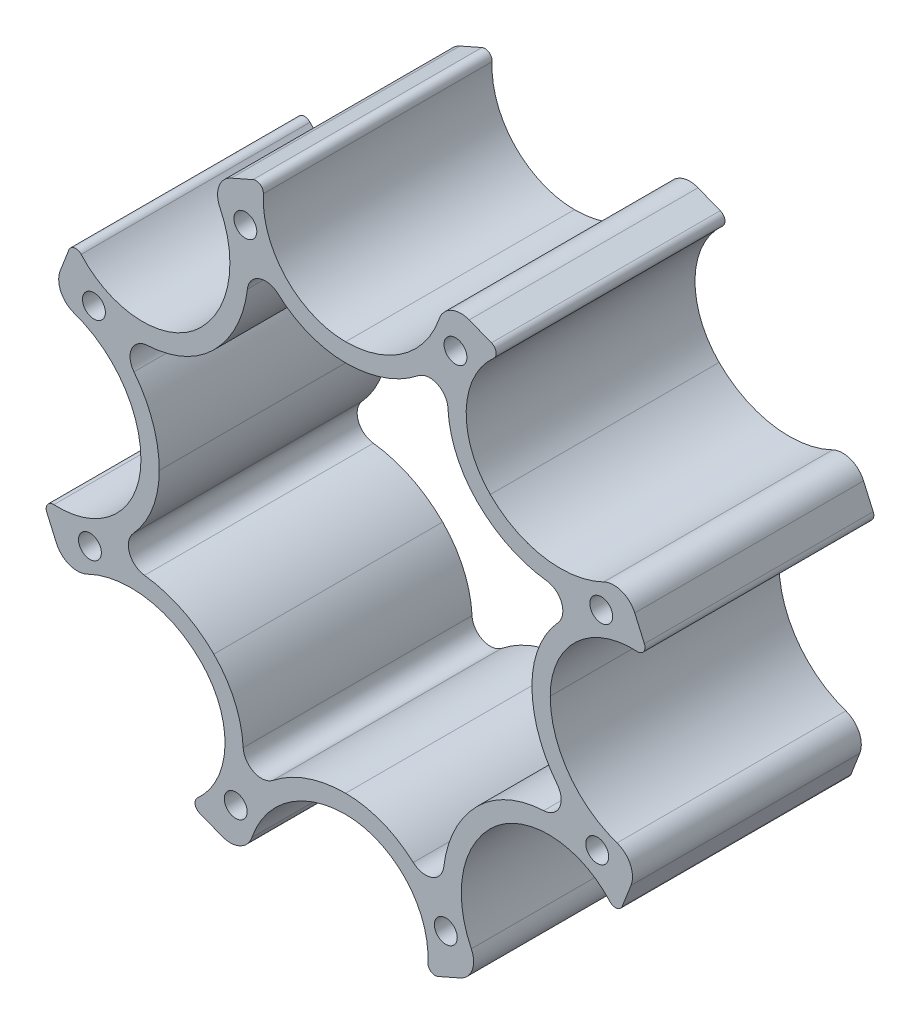
SolidWorks part; units mm, degrees
material "6061-T6 (SS)"
ref_plane "前视基准面" through (0, 0, 0) normal (0, 0, 1) x (1, 0, 0)
ref_plane "上视基准面" through (0, 0, 0) normal (0, 1, 0) x (1, 0, 0)
ref_plane "右视基准面" through (0, 0, 0) normal (1, 0, 0) x (0, 0, -1)
sketch "草图1" plane through (0, 0, 0) normal (0, 0, 1) x (1, 0, 0)
  line L0 (0, 31.3575) -> (0, 0) construction
  line L1 (0, 0) -> (22.1731, 22.1731) construction
  line L4 (0, 31.3575) -> (22.1731, 22.1731) construction
  line L6 (11.6409, 26.5357) -> (12.5976, 28.8454) construction
  line L7 (22.2808, 22.9688) -> (16.1797, 28.8872) construction
  line L8 (22.2808, 22.9688) -> (28.5472, 29.4288) construction
  line L9 (15.9368, 30.2296) -> (13.5034, 31.1755)
  line L17 (0, 33.18) -> (0, 31.3575) construction
  line L18 (32.6446, 10.1066) -> (31.5928, 12.4961)
  line L19 (30.2296, -15.9368) -> (31.1755, -13.5034)
  line L20 (10.1066, -32.6446) -> (12.4961, -31.5928)
  line L21 (-15.9368, -30.2296) -> (-13.5034, -31.1755)
  line L22 (-32.6446, -10.1066) -> (-31.5928, -12.4961)
  line L23 (-30.2296, 15.9368) -> (-31.1755, 13.5034)
  line L24 (-10.1066, 32.6446) -> (-12.4961, 31.5928)
  circle A0 centre (0, 0) radius 31.3575 construction
  arc A9 (16.1797, 28.8872) -> (15.8091, 15.8091) centre (22.1731, 22.1731) ccw
  circle A13 centre (0, 0) radius 41 construction
  arc A16 (16.1797, 28.8872) -> (15.9368, 30.2296) centre (15.6469, 29.484) ccw
  arc A17 (13.5034, 31.1755) -> (10.2336, 29.6588) centre (12.5976, 28.8454) ccw
  arc A18 (0, 22.3575) -> (10.2336, 29.6588) centre (0, 33.18) ccw
  arc A19 (15.8091, 15.8091) -> (28.2082, 13.7357) centre (23.4618, 23.4618) ccw
  arc A20 (31.5928, 12.4961) -> (28.2082, 13.7357) centre (29.3046, 11.4889) ccw
  arc A21 (31.8671, 8.9856) -> (32.6446, 10.1066) centre (31.9124, 9.7843) ccw
  arc A22 (31.8671, 8.9856) -> (22.3575, 0) centre (31.3575, 0) ccw
  arc A23 (22.3575, 0) -> (29.6588, -10.2336) centre (33.18, 0) ccw
  arc A24 (31.1755, -13.5034) -> (29.6588, -10.2336) centre (28.8454, -12.5976) ccw
  arc A25 (28.8872, -16.1797) -> (30.2296, -15.9368) centre (29.484, -15.6469) ccw
  arc A26 (28.8872, -16.1797) -> (15.8091, -15.8091) centre (22.1731, -22.1731) ccw
  arc A27 (15.8091, -15.8091) -> (13.7357, -28.2082) centre (23.4618, -23.4618) ccw
  arc A28 (12.4961, -31.5928) -> (13.7357, -28.2082) centre (11.4889, -29.3046) ccw
  arc A29 (8.9856, -31.8671) -> (10.1066, -32.6446) centre (9.7843, -31.9124) ccw
  arc A30 (8.9856, -31.8671) -> (0, -22.3575) centre (0, -31.3575) ccw
  arc A31 (0, -22.3575) -> (-10.2336, -29.6588) centre (0, -33.18) ccw
  arc A32 (-13.5034, -31.1755) -> (-10.2336, -29.6588) centre (-12.5976, -28.8454) ccw
  arc A33 (-16.1797, -28.8872) -> (-15.9368, -30.2296) centre (-15.6469, -29.484) ccw
  arc A34 (-16.1797, -28.8872) -> (-15.8091, -15.8091) centre (-22.1731, -22.1731) ccw
  arc A35 (-15.8091, -15.8091) -> (-28.2082, -13.7357) centre (-23.4618, -23.4618) ccw
  arc A36 (-31.5928, -12.4961) -> (-28.2082, -13.7357) centre (-29.3046, -11.4889) ccw
  arc A37 (-31.8671, -8.9856) -> (-32.6446, -10.1066) centre (-31.9124, -9.7843) ccw
  arc A38 (-31.8671, -8.9856) -> (-22.3575, 0) centre (-31.3575, 0) ccw
  arc A39 (-22.3575, 0) -> (-29.6588, 10.2336) centre (-33.18, 0) ccw
  arc A40 (-31.1755, 13.5034) -> (-29.6588, 10.2336) centre (-28.8454, 12.5976) ccw
  arc A41 (-28.8872, 16.1797) -> (-30.2296, 15.9368) centre (-29.484, 15.6469) ccw
  arc A42 (-28.8872, 16.1797) -> (-15.8091, 15.8091) centre (-22.1731, 22.1731) ccw
  arc A43 (-15.8091, 15.8091) -> (-13.7357, 28.2082) centre (-23.4618, 23.4618) ccw
  arc A44 (-12.4961, 31.5928) -> (-13.7357, 28.2082) centre (-11.4889, 29.3046) ccw
  arc A45 (-8.9856, 31.8671) -> (-10.1066, 32.6446) centre (-9.7843, 31.9124) ccw
  arc A46 (-8.9856, 31.8671) -> (0, 22.3575) centre (0, 31.3575) ccw
  point P91 (0, 0)
  point P98 (0, 0)
  dimension "D1" = 9
  dimension "D3" = 45
  dimension "D4" = 8
  dimension "D5" = 9
  dimension "D8" = 82
  dimension "D9" = 9
  dimension "D10" = 2.5
  dimension "D11" = 0.8
  dimension "D2" = 24
  dimension "D6" = 11.4
  dimension "D7" = 2.5
  dimension "D13" = 8.5
extrude "凸台-拉伸1" add sketch "草图1" along normal blind 25
sketch "草图2" plane through (0, 0, 0) normal (0, 0, -1) x (-1, 0, 0)
  line L0 (0, 0) -> (22.3575, 0) construction
  line L1 (0, 0) -> (15.8091, -15.8091) construction
  arc A0 (20.3575, 0) -> (23.2148, -7.3957) centre (31.3575, 0) ccw
  arc A1 (21.9674, -10.7267) -> (14.3949, -14.3949) centre (23.4618, -23.4618) ccw
  arc A2 (21.9674, -10.7267) -> (23.2148, -7.3957) centre (21.7343, -8.7403) ccw
  arc A3 (22.3575, 0) -> (31.8671, -8.9856) centre (31.3575, 0) ccw construction
  arc A4 (14.3949, -14.3949) -> (11.1858, -21.6449) centre (22.1731, -22.1731) ccw
  arc A5 (7.9484, -23.1182) -> (11.1858, -21.6449) centre (9.1881, -21.5488) ccw
  arc A27 (28.2082, -13.7357) -> (15.8091, -15.8091) centre (23.4618, -23.4618) ccw construction
  arc A28 (7.9484, -23.1182) -> (0, -20.3575) centre (0, -33.18) ccw
  arc A29 (0, -20.3575) -> (-7.3957, -23.2148) centre (0, -31.3575) ccw
  arc A30 (-10.7267, -21.9674) -> (-7.3957, -23.2148) centre (-8.7403, -21.7343) ccw
  arc A31 (-10.7267, -21.9674) -> (-14.3949, -14.3949) centre (-23.4618, -23.4618) ccw
  arc A32 (-14.3949, -14.3949) -> (-21.6449, -11.1858) centre (-22.1731, -22.1731) ccw
  arc A33 (-23.1182, -7.9484) -> (-21.6449, -11.1858) centre (-21.5488, -9.1881) ccw
  arc A34 (-23.1182, -7.9484) -> (-20.3575, 0) centre (-33.18, 0) ccw
  arc A35 (-20.3575, 0) -> (-23.2148, 7.3957) centre (-31.3575, 0) ccw
  arc A36 (-21.9674, 10.7267) -> (-23.2148, 7.3957) centre (-21.7343, 8.7403) ccw
  arc A37 (-21.9674, 10.7267) -> (-14.3949, 14.3949) centre (-23.4618, 23.4618) ccw
  arc A38 (-14.3949, 14.3949) -> (-11.1858, 21.6449) centre (-22.1731, 22.1731) ccw
  arc A39 (-7.9484, 23.1182) -> (-11.1858, 21.6449) centre (-9.1881, 21.5488) ccw
  arc A40 (-7.9484, 23.1182) -> (0, 20.3575) centre (0, 33.18) ccw
  arc A41 (0, 20.3575) -> (7.3957, 23.2148) centre (0, 31.3575) ccw
  arc A42 (10.7267, 21.9674) -> (7.3957, 23.2148) centre (8.7403, 21.7343) ccw
  arc A43 (10.7267, 21.9674) -> (14.3949, 14.3949) centre (23.4618, 23.4618) ccw
  arc A44 (14.3949, 14.3949) -> (21.6449, 11.1858) centre (22.1731, 22.1731) ccw
  arc A45 (23.1182, 7.9484) -> (21.6449, 11.1858) centre (21.5488, 9.1881) ccw
  arc A46 (23.1182, 7.9484) -> (20.3575, 0) centre (33.18, 0) ccw
  point P69 (0, 0)
  dimension "D1" = 2
  dimension "D2" = 2
  dimension "D3" = 2
  dimension "D4" = 8
extrude "切除-拉伸1" cut sketch "草图2" against normal through all
sketch "草图3" plane through (0, 0, 25) normal (0, 0, 1) x (1, 0, 0)
  line L8 (15.9368, 30.2296) -> (13.5034, 31.1755)
  line L9 (-10.1066, 32.6446) -> (-12.4961, 31.5928)
  line L10 (-30.2296, 15.9368) -> (-31.1755, 13.5034)
  line L11 (-32.6446, -10.1066) -> (-31.5928, -12.4961)
  line L12 (-15.9368, -30.2296) -> (-13.5034, -31.1755)
  line L13 (10.1066, -32.6446) -> (12.4961, -31.5928)
  line L14 (30.2296, -15.9368) -> (31.1755, -13.5034)
  line L15 (32.6446, 10.1066) -> (31.5928, 12.4961)
  line L16 (15.9368, 30.2296) -> (13.5034, 31.1755)
  line L17 (-10.1066, 32.6446) -> (-12.4961, 31.5928)
  line L18 (-30.2296, 15.9368) -> (-31.1755, 13.5034)
  line L19 (-32.6446, -10.1066) -> (-31.5928, -12.4961)
  line L20 (-15.9368, -30.2296) -> (-13.5034, -31.1755)
  line L21 (10.1066, -32.6446) -> (12.4961, -31.5928)
  line L22 (30.2296, -15.9368) -> (31.1755, -13.5034)
  line L23 (32.6446, 10.1066) -> (31.5928, 12.4961)
  arc A32 (15.8091, 15.8091) -> (28.2082, 13.7357) centre (23.4618, 23.4618) ccw
  arc A33 (16.1797, 28.8872) -> (15.8091, 15.8091) centre (22.1731, 22.1731) ccw
  arc A34 (16.1797, 28.8872) -> (15.9368, 30.2296) centre (15.6469, 29.484) ccw
  arc A35 (13.5034, 31.1755) -> (10.2336, 29.6588) centre (12.5976, 28.8454) ccw
  arc A36 (0, 22.3575) -> (10.2336, 29.6588) centre (0, 33.18) ccw
  arc A37 (-8.9856, 31.8671) -> (0, 22.3575) centre (0, 31.3575) ccw
  arc A38 (-8.9856, 31.8671) -> (-10.1066, 32.6446) centre (-9.7843, 31.9124) ccw
  arc A39 (-12.4961, 31.5928) -> (-13.7357, 28.2082) centre (-11.4889, 29.3046) ccw
  arc A40 (-15.8091, 15.8091) -> (-13.7357, 28.2082) centre (-23.4618, 23.4618) ccw
  arc A41 (-28.8872, 16.1797) -> (-15.8091, 15.8091) centre (-22.1731, 22.1731) ccw
  arc A42 (-28.8872, 16.1797) -> (-30.2296, 15.9368) centre (-29.484, 15.6469) ccw
  arc A43 (-31.1755, 13.5034) -> (-29.6588, 10.2336) centre (-28.8454, 12.5976) ccw
  arc A44 (-22.3575, 0) -> (-29.6588, 10.2336) centre (-33.18, 0) ccw
  arc A45 (-31.8671, -8.9856) -> (-22.3575, 0) centre (-31.3575, 0) ccw
  arc A46 (-31.8671, -8.9856) -> (-32.6446, -10.1066) centre (-31.9124, -9.7843) ccw
  arc A47 (-31.5928, -12.4961) -> (-28.2082, -13.7357) centre (-29.3046, -11.4889) ccw
  arc A48 (-15.8091, -15.8091) -> (-28.2082, -13.7357) centre (-23.4618, -23.4618) ccw
  arc A49 (-16.1797, -28.8872) -> (-15.8091, -15.8091) centre (-22.1731, -22.1731) ccw
  arc A50 (-16.1797, -28.8872) -> (-15.9368, -30.2296) centre (-15.6469, -29.484) ccw
  arc A51 (-13.5034, -31.1755) -> (-10.2336, -29.6588) centre (-12.5976, -28.8454) ccw
  arc A52 (0, -22.3575) -> (-10.2336, -29.6588) centre (0, -33.18) ccw
  arc A53 (8.9856, -31.8671) -> (0, -22.3575) centre (0, -31.3575) ccw
  arc A54 (8.9856, -31.8671) -> (10.1066, -32.6446) centre (9.7843, -31.9124) ccw
  arc A55 (12.4961, -31.5928) -> (13.7357, -28.2082) centre (11.4889, -29.3046) ccw
  arc A56 (15.8091, -15.8091) -> (13.7357, -28.2082) centre (23.4618, -23.4618) ccw
  arc A57 (28.8872, -16.1797) -> (15.8091, -15.8091) centre (22.1731, -22.1731) ccw
  arc A58 (28.8872, -16.1797) -> (30.2296, -15.9368) centre (29.484, -15.6469) ccw
  arc A59 (31.1755, -13.5034) -> (29.6588, -10.2336) centre (28.8454, -12.5976) ccw
  arc A60 (22.3575, 0) -> (29.6588, -10.2336) centre (33.18, 0) ccw
  arc A61 (31.8671, 8.9856) -> (22.3575, 0) centre (31.3575, 0) ccw
  arc A62 (31.8671, 8.9856) -> (32.6446, 10.1066) centre (31.9124, 9.7843) ccw
  arc A63 (31.5928, 12.4961) -> (28.2082, 13.7357) centre (29.3046, 11.4889) ccw
  arc A64 (15.8091, 15.8091) -> (28.2082, 13.7357) centre (23.4618, 23.4618) ccw
  arc A65 (16.1797, 28.8872) -> (15.8091, 15.8091) centre (22.1731, 22.1731) ccw
  arc A66 (16.1797, 28.8872) -> (15.9368, 30.2296) centre (15.6469, 29.484) ccw
  arc A67 (13.5034, 31.1755) -> (10.2336, 29.6588) centre (12.5976, 28.8454) ccw
  arc A68 (0, 22.3575) -> (10.2336, 29.6588) centre (0, 33.18) ccw
  arc A69 (-8.9856, 31.8671) -> (0, 22.3575) centre (0, 31.3575) ccw
  arc A70 (-8.9856, 31.8671) -> (-10.1066, 32.6446) centre (-9.7843, 31.9124) ccw
  arc A71 (-12.4961, 31.5928) -> (-13.7357, 28.2082) centre (-11.4889, 29.3046) ccw
  arc A72 (-15.8091, 15.8091) -> (-13.7357, 28.2082) centre (-23.4618, 23.4618) ccw
  arc A73 (-28.8872, 16.1797) -> (-15.8091, 15.8091) centre (-22.1731, 22.1731) ccw
  arc A74 (-28.8872, 16.1797) -> (-30.2296, 15.9368) centre (-29.484, 15.6469) ccw
  arc A75 (-31.1755, 13.5034) -> (-29.6588, 10.2336) centre (-28.8454, 12.5976) ccw
  arc A76 (-22.3575, 0) -> (-29.6588, 10.2336) centre (-33.18, 0) ccw
  arc A77 (-31.8671, -8.9856) -> (-22.3575, 0) centre (-31.3575, 0) ccw
  arc A78 (-31.8671, -8.9856) -> (-32.6446, -10.1066) centre (-31.9124, -9.7843) ccw
  arc A79 (-31.5928, -12.4961) -> (-28.2082, -13.7357) centre (-29.3046, -11.4889) ccw
  arc A80 (-15.8091, -15.8091) -> (-28.2082, -13.7357) centre (-23.4618, -23.4618) ccw
  arc A81 (-16.1797, -28.8872) -> (-15.8091, -15.8091) centre (-22.1731, -22.1731) ccw
  arc A82 (-16.1797, -28.8872) -> (-15.9368, -30.2296) centre (-15.6469, -29.484) ccw
  arc A83 (-13.5034, -31.1755) -> (-10.2336, -29.6588) centre (-12.5976, -28.8454) ccw
  arc A84 (0, -22.3575) -> (-10.2336, -29.6588) centre (0, -33.18) ccw
  arc A85 (8.9856, -31.8671) -> (0, -22.3575) centre (0, -31.3575) ccw
  arc A86 (8.9856, -31.8671) -> (10.1066, -32.6446) centre (9.7843, -31.9124) ccw
  arc A87 (12.4961, -31.5928) -> (13.7357, -28.2082) centre (11.4889, -29.3046) ccw
  arc A88 (15.8091, -15.8091) -> (13.7357, -28.2082) centre (23.4618, -23.4618) ccw
  arc A89 (28.8872, -16.1797) -> (15.8091, -15.8091) centre (22.1731, -22.1731) ccw
  arc A90 (28.8872, -16.1797) -> (30.2296, -15.9368) centre (29.484, -15.6469) ccw
  arc A91 (31.1755, -13.5034) -> (29.6588, -10.2336) centre (28.8454, -12.5976) ccw
  arc A92 (22.3575, 0) -> (29.6588, -10.2336) centre (33.18, 0) ccw
  arc A93 (31.8671, 8.9856) -> (22.3575, 0) centre (31.3575, 0) ccw
  arc A94 (31.8671, 8.9856) -> (32.6446, 10.1066) centre (31.9124, 9.7843) ccw
  arc A95 (31.5928, 12.4961) -> (28.2082, 13.7357) centre (29.3046, 11.4889) ccw
  dimension "D1" = 0
extrude "凸台-拉伸2" add sketch "草图3" along normal blind 4
sketch "草图4" plane through (0, 0, 29) normal (0, 0, 1) x (1, 0, 0)
  line L0 (0, 0) -> (8, 0) construction
  line L1 (0, 0) -> (-9.235, 17.7402) construction
  circle A0 centre (0, 0) radius 3.5
  circle A1 centre (8, 0) radius 1.7
  circle A2 centre (0, -8) radius 1.7
  circle A3 centre (-8, 0) radius 1.7
  circle A4 centre (0, 8) radius 1.7
  circle A5 centre (-9.235, 17.7402) radius 2.3
  circle A6 centre (17.7402, 9.235) radius 2.3
  circle A7 centre (9.235, -17.7402) radius 2.3
  circle A8 centre (-17.7402, -9.235) radius 2.3
  point P14 (0, 0)
  point P22 (0, 0)
  dimension "D1" = 7
  dimension "D2" = 3.4
  dimension "D6" = 4.6
  dimension "D3" = 8
  dimension "D5" = 20
  dimension "D7" = 62.5
  dimension "D4" = 4
  dimension "D8" = 4
extrude "切除-拉伸2" cut sketch "草图4" against normal through all
sketch "草图5" plane through (0, 0, 29) normal (0, 0, 1) x (1, 0, 0)
  circle A0 centre (0, 0) radius 50
  dimension "D1" = 100
extrude "切除-拉伸3" cut sketch "草图5" against normal blind 4
hole_wizard "M3 螺纹孔1" positions "草图8" profile "草图7" tap size "M3" standard "GB"
sketch "草图8" plane through (0, 0, 25) normal (0, 0, 1) x (1, 0, 0)
  line L0 (-11.4889, 29.3046) -> (0, 0) construction
  line L2 (0, 0) -> (-30, 0) construction
  circle A0 centre (0, 0) radius 30 construction
  point P0 (-10.9501, 27.9302)
  point P35 (12.0067, 27.4925)
  point P36 (27.9302, 10.9501)
  point P37 (27.4925, -12.0067)
  point P38 (10.9501, -27.9302)
  point P39 (-12.0067, -27.4925)
  point P40 (-27.9302, -10.9501)
  point P41 (-27.4925, 12.0067)
  dimension "D2" = 60
  dimension "D3" = 8
cosmetic thread "孔螺纹线1" parameters "D1"=10, "D2"=3
sketch "草图7" plane through (-10.9501, 27.9302, 25) normal (1, 0, 0) x (0, -1, 0)
  line L0 (0, 0) -> (0, 12.2511)
  line L1 (0, 12.2511) -> (1.25, 11.5)
  line L2 (1.25, 11.5) -> (1.25, 0)
  line L5 (1.25, 0) -> (0, 0)
  line L10 (0, 12.2511) -> (-1.25, 11.5) construction
  line L11 (0, -6.35) -> (0, 107.95) construction
  dimension "螺纹孔钻头直径" = 2.5
  dimension "螺纹孔钻头深度" = 11.5
  dimension "导头角度" = 118
cosmetic thread "孔螺纹线2" parameters "D1"=10, "D2"=3
cosmetic thread "孔螺纹线3" parameters "D1"=10, "D2"=3
cosmetic thread "孔螺纹线4" parameters "D1"=10, "D2"=3
cosmetic thread "孔螺纹线5" parameters "D1"=10, "D2"=3
cosmetic thread "孔螺纹线6" parameters "D1"=10, "D2"=3
cosmetic thread "孔螺纹线7" parameters "D1"=10, "D2"=3
cosmetic thread "孔螺纹线8" parameters "D1"=10, "D2"=3
